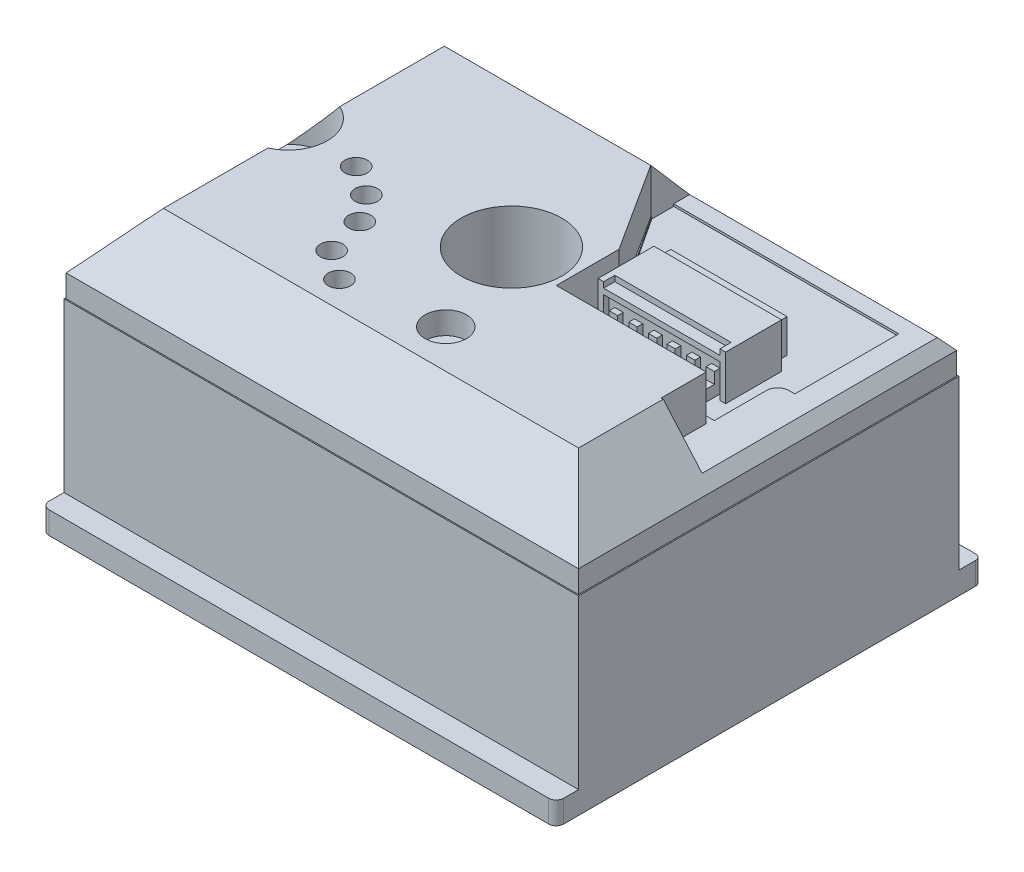
SolidWorks part; units mm, degrees
ref_plane "Front Plane" through (0, 0, 0) normal (0, 0, 1) x (1, 0, 0)
ref_plane "Top Plane" through (0, 0, 0) normal (0, 1, 0) x (1, 0, 0)
ref_plane "Right Plane" through (0, 0, 0) normal (1, 0, 0) x (0, 0, -1)
sketch "Sketch1" plane through (0, 0, 0) normal (0, 1, 0) x (1, 0, 0)
  line L0 (23, 34) -> (23, 0) construction
  line L1 (0, 0) -> (46, 0)
  line L2 (0, 0) -> (0, 34)
  line L3 (0, 34) -> (46, 34)
  line L4 (46, 0) -> (46, 34)
  line L5 (0, 17) -> (46, 17) construction
  circle A0 centre (23, 17) radius 4.5
  dimension "D2" = 9
  dimension "D1" = 46
  dimension "D5" = 34
extrude "Boss-Extrude1" add sketch "Sketch1" along normal blind 17
sketch "Sketch2" plane through (0, 17, 0) normal (0, 1, 0) x (1, 0, 0)
  line L8 (0.1, 0.1) -> (45.9, 0.1)
  line L9 (45.9, 0.1) -> (45.9, 33.9)
  line L10 (45.9, 33.9) -> (0.1, 33.9)
  line L11 (0.1, 33.9) -> (0.1, 0.1)
  line L12 (0.1, 0.1) -> (45.9, 0.1)
  line L13 (45.9, 0.1) -> (45.9, 33.9)
  line L14 (45.9, 33.9) -> (0.1, 33.9)
  line L15 (0.1, 33.9) -> (0.1, 0.1)
  dimension "D1" = 0.1
extrude "Boss-Extrude2" add sketch "Sketch2" along normal blind 2
sketch "Sketch3" plane through (0, 19, 0) normal (0, 1, 0) x (1, 0, 0)
  line L4 (0.1, 33.9) -> (0.1, 0.1)
  line L5 (0.1, 0.1) -> (45.9, 0.1)
  line L6 (45.9, 0.1) -> (45.9, 33.9)
  line L7 (45.9, 33.9) -> (0.1, 33.9)
  line L8 (0.1, 33.9) -> (0.1, 0.1)
  line L9 (0.1, 0.1) -> (45.9, 0.1)
  line L10 (45.9, 0.1) -> (45.9, 33.9)
  line L11 (45.9, 33.9) -> (0.1, 33.9)
  dimension "D1" = 0
extrude "Boss-Extrude3" add sketch "Sketch3" along normal blind 5
chamfer "Chamfer1" distance 5 angle 41 4 edges at (45.9, 24, -17) (23, 24, -33.9) (0.1, 24, -17) (23, 24, -0.1)
sketch "Sketch5" plane through (0, 24, 0) normal (0, 1, 0) x (1, 0, 0)
  circle A0 centre (23, 17) radius 4.5 construction
  circle A1 centre (23, 17) radius 4.5
extrude "Cut-Extrude1" cut sketch "Sketch5" against normal through all
sketch "Sketch7" plane through (0, 24, 0) normal (0, 1, 0) x (1, 0, 0)
  line L0 (45.9, 33.9) -> (45.9, 0.1) construction
  line L1 (45.9, 0.1) -> (0.1, 0.1) construction
  line L2 (0.1, 0.1) -> (0.1, 33.9) construction
  line L3 (0, 34) -> (46, 34) construction
  line L4 (45.9, 33.9) -> (45.9, 0.1)
  line L5 (45.9, 0.1) -> (0.1, 0.1)
  line L6 (0.1, 0.1) -> (0.1, 33.9)
  line L7 (0, 34) -> (46, 34)
  line L8 (45.9, 33.9) -> (45.9, 12.0117)
  line L9 (45.9, 12.0117) -> (41.3759, 12.0117)
  line L10 (41.3759, 12.0117) -> (41.3759, 16.0373)
  line L11 (41.3759, 16.0373) -> (27.9759, 16.0373)
  line L12 (4.4464, 4.4464) -> (41.5536, 4.4464)
  line L13 (41.5536, 4.4464) -> (41.5536, 29.5536)
  line L14 (41.5536, 29.5536) -> (4.4464, 29.5536)
  line L15 (4.4464, 29.5536) -> (4.4464, 4.4464)
  line L16 (4.4464, 4.4464) -> (41.5536, 4.4464)
  line L17 (41.5536, 4.4464) -> (41.5536, 29.5536)
  line L18 (41.5536, 29.5536) -> (4.4464, 29.5536)
  line L19 (4.4464, 29.5536) -> (4.4464, 4.4464)
  line L20 (27.9759, 16.0373) -> (27.9759, 21.6383)
  line L21 (27.9759, 21.6383) -> (22.9, 29.5536)
  line L22 (22.9, 29.5536) -> (22.9, 34)
  line L23 (22.9, 34) -> (45.9, 33.9)
  line L24 (45.9, 12.0117) -> (45.9, 33.9)
  line M14 (41.5536, 4.4464) -> (41.5536, 29.5536)
  line M15 (41.5536, 29.5536) -> (4.4464, 29.5536)
  dimension "D2" = 22.8
  dimension "D3" = 13.4
  dimension "D4" = 21.9883
  dimension "D5" = 17.9627
  dimension "D6" = 17.9241
  dimension "D7" = 12.3617
  dimension "D1" = 0
extrude "Cut-Extrude2" cut sketch "Sketch7" against normal blind 4 contours L21 L20 L11 L10 L9 M14 M15 | L23 L22 L9 L4 M15 M14
sketch "Sketch9" plane through (0, 24, 0) normal (0, 1, 0) x (1, 0, 0)
  line L0 (45.9, 33.9) -> (45.9, 0.1) construction
  line L1 (45.9, 0.1) -> (0.1, 0.1) construction
  line L2 (45.9, 33.9) -> (0.1, 33.9) construction
  line L3 (0.1, 0.1) -> (0.1, 33.9) construction
  line L4 (45.9, 33.9) -> (45.9, 0.1)
  line L5 (45.9, 0.1) -> (0.1, 0.1)
  line L6 (45.9, 33.9) -> (0.1, 33.9)
  line L7 (0.1, 0.1) -> (0.1, 33.9)
  line L8 (0.1, 17) -> (45.9, 17) construction
  line L9 (0.1, 18.9) -> (0.1, 15.1)
  line L10 (0.1, 18.9) -> (0.1, 15.1)
  arc A0 (0.1, 18.9) -> (0.1, 15.1) centre (3.0394, 17) cw
  dimension "D1" = 15
  dimension "D2" = 3.5
extrude "Cut-Extrude3" cut sketch "Sketch9" against normal blind 4.5 contours L10 L8 L3 A0 | L3 L8 A0 | L8 L3 A0 | L8 L7 A0 L3
sketch "Sketch10" plane through (0, 20, 0) normal (0, 1, 0) x (1, 0, 0)
  line L0 (45.0307, 33.0307) -> (45.0307, 12.0117) construction
  line L1 (0.1, 33.9) -> (45.9, 33.9) construction
  line L9 (43.0307, 22.3) -> (42.5, 22.3)
  line L10 (41.5, 21.3) -> (41.5, 16.6415)
  line L11 (0.1, 0.1) -> (0.1, 33.9) construction
  line L24 (22.9, 31.6) -> (22.9, 29.6415)
  line L25 (22.9, 29.6415) -> (28.1, 21.7262)
  line L26 (28.1, 21.7262) -> (28.1, 16.6415)
  line L27 (28.1, 16.6415) -> (41.5, 16.6415)
  line L30 (43.0307, 22.3) -> (43.0307, 31.6)
  line L31 (43.0307, 31.6) -> (22.9, 31.6)
  arc A0 (42.5, 22.3) -> (41.5, 21.3) centre (42.5, 21.3) ccw
  dimension "D1" = 13
  dimension "D2" = 13.4
  dimension "D3" = 28
  dimension "D4" = 22.8
  dimension "D5" = 2.3
  dimension "D6" = 2
extrude "Cut-Extrude4" cut sketch "Sketch10" against normal blind 0.2
sketch "Sketch11" plane through (0, 19.8, 0) normal (0, 1, 0) x (1, 0, 0)
  line L0 (41.5, 16.6415) -> (41.5, 21.3) construction
  line L1 (29.1, 18.6415) -> (40.5, 18.6415)
  line L2 (29.1, 18.6415) -> (29.1, 23.6415)
  line L3 (29.1, 23.6415) -> (40.5, 23.6415)
  line L4 (40.5, 18.6415) -> (40.5, 23.6415)
  line L5 (28.1, 21.7262) -> (28.1, 16.6415) construction
  line L6 (28.1, 16.6415) -> (41.5, 16.6415) construction
  dimension "D1" = 1
  dimension "D2" = 1
  dimension "D3" = 5
  dimension "D4" = 2
extrude "Boss-Extrude4" add sketch "Sketch11" along normal blind 4
sketch "Sketch12" plane through (0, 23.8, 0) normal (0, 1, 0) x (1, 0, 0)
  line L0 (29.1, 18.6415) -> (40.5, 18.6415) construction
  line L1 (29.6, 18.6415) -> (40, 18.6415)
  line L2 (29.6, 18.6415) -> (29.6, 19.6415)
  line L3 (29.6, 19.6415) -> (40, 19.6415)
  line L4 (40, 18.6415) -> (40, 19.6415)
  line L5 (29.1, 23.6415) -> (29.1, 18.6415) construction
  line L6 (40.5, 18.6415) -> (40.5, 23.6415) construction
  dimension "D1" = 0.5
  dimension "D2" = 0.5
  dimension "D3" = 1
extrude "Cut-Extrude5" cut sketch "Sketch12" against normal blind 0.5
sketch "Sketch13" plane through (0, 0, -18.6415) normal (0, 0, 1) x (1, 0, 0)
  line L0 (29.1, 19.8) -> (40.5, 19.8) construction
  line L1 (29.6, 19.8) -> (40, 19.8)
  line L2 (29.6, 19.8) -> (29.6, 22.8)
  line L3 (29.6, 22.8) -> (40, 22.8)
  line L4 (40, 19.8) -> (40, 22.8)
  line L6 (29.1, 23.8) -> (29.1, 19.8) construction
  line L7 (40.5, 23.8) -> (40.5, 19.8) construction
  line L8 (40, 23.3) -> (29.6, 23.3) construction
  dimension "D1" = 0.5
  dimension "D2" = 0.5
  dimension "D3" = 0.5
extrude "Cut-Extrude6" cut sketch "Sketch13" against normal blind 0.5
sketch "Sketch14" plane through (0, 0, -19.1415) normal (0, 0, 1) x (1, 0, 0)
  line L0 (29.6, 19.8) -> (40, 19.8) construction
  line L1 (30.1, 19.8) -> (30.85, 19.8)
  line L2 (30.1, 19.8) -> (30.1, 21.8)
  line L3 (30.1, 21.8) -> (30.85, 21.8)
  line L4 (30.85, 19.8) -> (30.85, 21.8)
  line L5 (40, 19.8) -> (40, 22.8) construction
  line L6 (31.85, 19.8) -> (32.6, 19.8)
  line L7 (31.85, 19.8) -> (31.85, 21.8)
  line L8 (31.85, 21.8) -> (32.6, 21.8)
  line L9 (32.6, 19.8) -> (32.6, 21.8)
  line L10 (33.6, 19.8) -> (34.35, 19.8)
  line L11 (33.6, 19.8) -> (33.6, 21.8)
  line L12 (33.6, 21.8) -> (34.35, 21.8)
  line L13 (34.35, 19.8) -> (34.35, 21.8)
  line L14 (35.25, 19.8) -> (36, 19.8)
  line L15 (35.25, 19.8) -> (35.25, 21.8)
  line L16 (35.25, 21.8) -> (36, 21.8)
  line L17 (36, 19.8) -> (36, 21.8)
  line L18 (37, 19.8) -> (37.75, 19.8)
  line L19 (37, 19.8) -> (37, 21.8)
  line L20 (37, 21.8) -> (37.75, 21.8)
  line L21 (37.75, 19.8) -> (37.75, 21.8)
  line L22 (38.75, 19.8) -> (39.5, 19.8)
  line L23 (38.75, 19.8) -> (38.75, 21.8)
  line L24 (38.75, 21.8) -> (39.5, 21.8)
  line L25 (39.5, 19.8) -> (39.5, 21.8)
  line L26 (29.6, 22.8) -> (29.6, 19.8) construction
  dimension "D1" = 0.75
  dimension "D2" = 0.5
  dimension "D3" = 1
  dimension "D4" = 1
  dimension "D5" = 0.5
  dimension "D6" = 1
  dimension "D7" = 1
  dimension "D8" = 2
extrude "Boss-Extrude5" add sketch "Sketch14" along normal blind 0.5
sketch "Sketch15" plane through (0, 0, -18.6415) normal (0, 0, 1) x (1, 0, 0)
  line L0 (30.85, 19.8) -> (30.85, 21.8) construction
  line L1 (30.1, 19.8) -> (30.85, 19.8)
  line L2 (30.1, 19.8) -> (30.1, 20.8)
  line L3 (30.1, 20.8) -> (30.85, 20.8)
  line L4 (30.85, 19.8) -> (30.85, 20.8)
  line L5 (32.6, 19.8) -> (32.6, 21.8) construction
  line L6 (31.85, 19.8) -> (32.6, 19.8)
  line L7 (31.85, 19.8) -> (31.85, 20.8)
  line L8 (31.85, 20.8) -> (32.6, 20.8)
  line L9 (32.6, 19.8) -> (32.6, 20.8)
  line L10 (34.35, 19.8) -> (34.35, 21.8) construction
  line L11 (33.6, 19.8) -> (34.35, 19.8)
  line L12 (33.6, 19.8) -> (33.6, 20.8)
  line L13 (33.6, 20.8) -> (34.35, 20.8)
  line L14 (34.35, 19.8) -> (34.35, 20.8)
  line L15 (36, 19.8) -> (36, 21.8) construction
  line L16 (35.25, 19.8) -> (36, 19.8)
  line L17 (35.25, 19.8) -> (35.25, 20.8)
  line L18 (35.25, 20.8) -> (36, 20.8)
  line L19 (36, 19.8) -> (36, 20.8)
  line L20 (37.75, 19.8) -> (37.75, 21.8) construction
  line L21 (37, 19.8) -> (37.75, 19.8)
  line L22 (37, 19.8) -> (37, 20.8)
  line L23 (37, 20.8) -> (37.75, 20.8)
  line L24 (37.75, 19.8) -> (37.75, 20.8)
  line L25 (39.5, 19.8) -> (39.5, 21.8) construction
  line L26 (38.75, 19.8) -> (39.5, 19.8)
  line L27 (38.75, 19.8) -> (38.75, 20.8)
  line L28 (38.75, 20.8) -> (39.5, 20.8)
  line L29 (39.5, 19.8) -> (39.5, 20.8)
extrude "Boss-Extrude6" add sketch "Sketch15" along normal blind 1
sketch "Sketch16" plane through (0, 0, -23.6415) normal (0, 0, -1) x (-1, 0, 0)
  line L8 (-40, 20.3) -> (-29.6, 20.3)
  line L9 (-29.6, 20.3) -> (-29.6, 23.3)
  line L10 (-29.6, 23.3) -> (-40, 23.3)
  line L11 (-40, 23.3) -> (-40, 20.3)
  line L12 (-40, 20.3) -> (-29.6, 20.3)
  line L13 (-29.6, 20.3) -> (-29.6, 23.3)
  line L14 (-29.6, 23.3) -> (-40, 23.3)
  line L15 (-40, 23.3) -> (-40, 20.3)
  dimension "D1" = 0.5
extrude "Boss-Extrude7" add sketch "Sketch16" along normal blind 1
sketch "Sketch18" plane through (0, 0, -24.6415) normal (0, 0, -1) x (-1, 0, 0)
  line L0 (-38.5, 22.8515) -> (-37.6412, 22.8515)
  line L1 (-37.6412, 22.8515) -> (-37.6412, 21.6227)
  line L2 (-37.6412, 21.6227) -> (-37.883, 21.6227)
  line L3 (-37.883, 21.6227) -> (-37.883, 21.05)
  line L4 (-37.883, 21.05) -> (-38.2582, 21.05)
  line L5 (-38.2582, 21.05) -> (-38.2582, 21.6227)
  line L6 (-38.5, 22.8515) -> (-38.5, 21.6227)
  line L7 (-38.5, 21.6227) -> (-38.2582, 21.6227)
  line L8 (-29.6, 23.3) -> (-40, 23.3) construction
  line L9 (-35.7825, 22.8515) -> (-34.9237, 22.8515)
  line L10 (-40, 23.3) -> (-40, 20.3) construction
  line L11 (-29.6, 20.3) -> (-29.6, 23.3) construction
  line L12 (-37.1412, 22.8515) -> (-36.2825, 22.8515)
  line L13 (-36.2825, 22.8515) -> (-36.2825, 21.6227)
  line L14 (-36.2825, 21.6227) -> (-36.5243, 21.6227)
  line L15 (-36.5243, 21.6227) -> (-36.5243, 21.05)
  line L16 (-36.5243, 21.05) -> (-36.8995, 21.05)
  line L17 (-36.8995, 21.05) -> (-36.8995, 21.6227)
  line L18 (-37.1412, 22.8515) -> (-37.1412, 21.6227)
  line L19 (-37.1412, 21.6227) -> (-36.8995, 21.6227)
  line L20 (-34.9237, 22.8515) -> (-34.9237, 21.6227)
  line L21 (-34.9237, 21.6227) -> (-35.1655, 21.6227)
  line L22 (-35.1655, 21.6227) -> (-35.1655, 21.05)
  line L23 (-35.1655, 21.05) -> (-35.5407, 21.05)
  line L24 (-35.5407, 21.05) -> (-35.5407, 21.6227)
  line L25 (-35.7825, 22.8515) -> (-35.7825, 21.6227)
  line L26 (-35.7825, 21.6227) -> (-35.5407, 21.6227)
  line L27 (-40, 21.8) -> (-29.6, 21.8) construction
  line L28 (-34.4237, 22.8515) -> (-33.565, 22.8515)
  line L29 (-33.565, 22.8515) -> (-33.565, 21.6227)
  line L30 (-33.565, 21.6227) -> (-33.8068, 21.6227)
  line L31 (-33.8068, 21.6227) -> (-33.8068, 21.05)
  line L32 (-33.8068, 21.05) -> (-34.182, 21.05)
  line L33 (-34.182, 21.05) -> (-34.182, 21.6227)
  line L34 (-34.4237, 22.8515) -> (-34.4237, 21.6227)
  line L35 (-34.4237, 21.6227) -> (-34.182, 21.6227)
  line L36 (-40, 23.3) -> (-40, 20.3) construction
  line L37 (-33.065, 22.8515) -> (-32.2062, 22.8515)
  line L38 (-32.2062, 22.8515) -> (-32.2062, 21.6227)
  line L39 (-32.2062, 21.6227) -> (-32.448, 21.6227)
  line L40 (-32.448, 21.6227) -> (-32.448, 21.05)
  line L41 (-32.448, 21.05) -> (-32.8232, 21.05)
  line L42 (-32.8232, 21.05) -> (-32.8232, 21.6227)
  line L43 (-33.065, 22.8515) -> (-33.065, 21.6227)
  line L44 (-33.065, 21.6227) -> (-32.8232, 21.6227)
  line L45 (-29.6, 20.3) -> (-29.6, 23.3) construction
  line L46 (-31.7062, 22.8515) -> (-30.8475, 22.8515)
  line L47 (-30.8475, 22.8515) -> (-30.8475, 21.6227)
  line L48 (-30.8475, 21.6227) -> (-31.0893, 21.6227)
  line L49 (-31.0893, 21.6227) -> (-31.0893, 21.05)
  line L50 (-31.0893, 21.05) -> (-31.4645, 21.05)
  line L51 (-31.4645, 21.05) -> (-31.4645, 21.6227)
  line L52 (-31.7062, 22.8515) -> (-31.7062, 21.6227)
  line L53 (-31.7062, 21.6227) -> (-31.4645, 21.6227)
  line L54 (-40, 20.3) -> (-29.6, 20.3) construction
  dimension "D1" = 0.4485
  dimension "D2" = 0.5
  dimension "D3" = 0.5
  dimension "D4" = 0.5
  dimension "D5" = 0.5
  dimension "D6" = 0.5
  dimension "D7" = 1.5
  dimension "D8" = 1.2475
  dimension "D9" = 0.75
extrude "Cut-Extrude7" cut sketch "Sketch18" against normal blind 1
sketch "Sketch19" plane through (0, 24, 0) normal (0, 1, 0) x (1, 0, 0)
  line L0 (4.4464, 4.4464) -> (41.5536, 4.4464) construction
  arc A0 (6.5394, 17) -> (14.4611, 4.4464) centre (6.3448, 8.101) cw construction
  arc A1 (4.4464, 13.7953) -> (4.4464, 20.2047) centre (3.0394, 17) ccw construction
  circle A2 centre (9.8229, 16.2945) radius 1
  circle A3 centre (12.4797, 14.5503) radius 1
  circle A4 centre (14.2489, 12.1943) radius 1
  circle A5 centre (15.2254, 8.7048) radius 1
  circle A6 centre (17.8119, 6.8132) radius 1
  dimension "D1" = 8.9011
  dimension "D2" = 2
  dimension "D3" = 4.2584
  dimension "D4" = 10.0146
extrude "Cut-Extrude8" cut sketch "Sketch19" against normal blind 2
sketch "Sketch20" plane through (0, 24, 0) normal (0, 1, 0) x (1, 0, 0)
  circle A0 centre (26.2288, 7.9016) radius 1.8488
extrude "Cut-Extrude9" cut sketch "Sketch20" against normal blind 2
sketch "Sketch21" plane through (0, 0, 0) normal (0, -1, 0) x (1, 0, 0)
  line L1 (46, -34) -> (22.9481, -34)
  line L2 (46, -34) -> (46, -35.5)
  line L3 (45.5, -36) -> (23.4481, -36)
  line L4 (22.9481, -34) -> (22.9481, -35.5)
  arc A0 (46, -35.5) -> (45.5, -36) centre (45.5, -35.5) cw
  arc A1 (23.4481, -36) -> (22.9481, -35.5) centre (23.4481, -35.5) cw
  dimension "D2" = 0.5
  dimension "D1" = 2
  dimension "D3" = 23.0519
extrude "Boss-Extrude8" add sketch "Sketch21" against normal blind 2
sketch "Sketch22" plane through (0, 0, 0) normal (0, -1, 0) x (1, 0, 0)
  line L1 (46, 0) -> (0, 0)
  line L2 (46, 0) -> (46, 1.3284)
  line L3 (45.3284, 2) -> (0.6716, 2)
  line L4 (0, 0) -> (0, 1.3284)
  arc A0 (46, 1.3284) -> (45.3284, 2) centre (45.3284, 1.3284) ccw
  arc A1 (0.6716, 2) -> (0, 1.3284) centre (0.6716, 1.3284) ccw
  dimension "D2" = 0.6716
  dimension "D3" = 44.6567
  dimension "D1" = 2
extrude "Boss-Extrude9" add sketch "Sketch22" against normal blind 2
